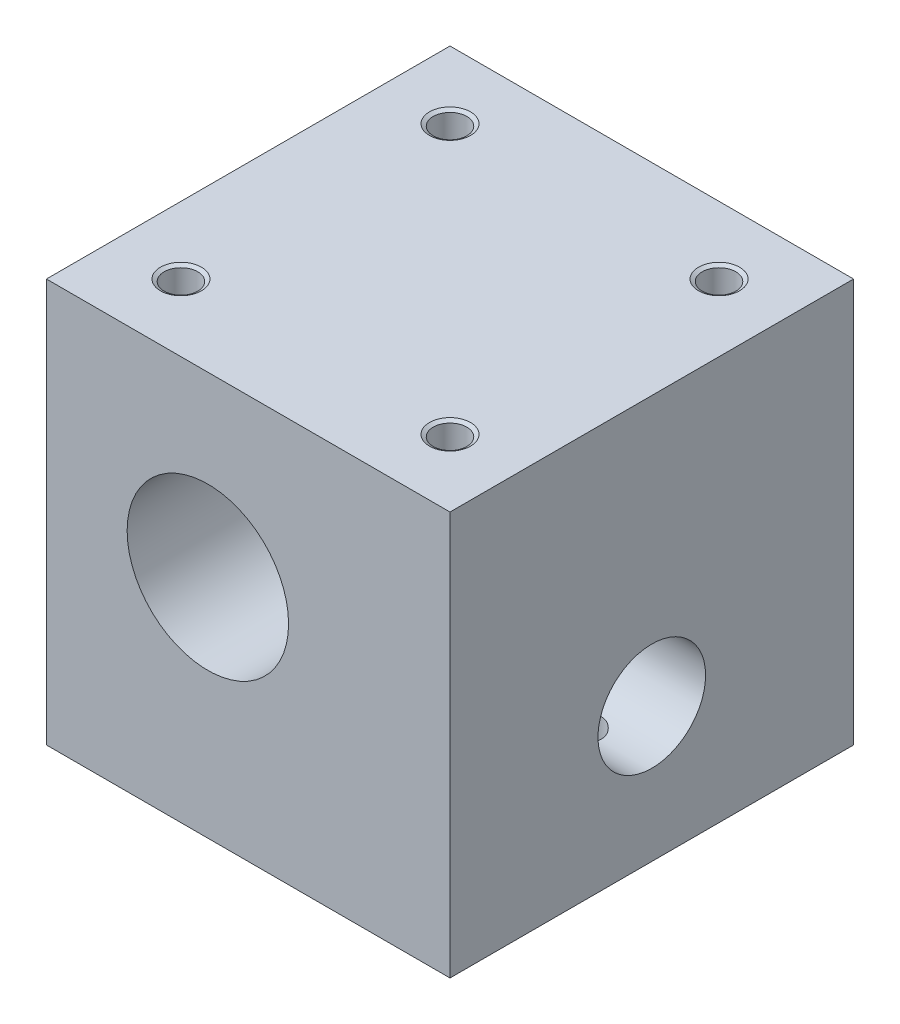
SolidWorks part; units mm, degrees
material "Lega 1060"
ref_plane "Piano frontale" through (0, 0, 0) normal (0, 0, 1) x (1, 0, 0)
ref_plane "Piano superiore" through (0, 0, 0) normal (0, 1, 0) x (1, 0, 0)
ref_plane "Piano destro" through (0, 0, 0) normal (1, 0, 0) x (0, 0, -1)
sketch "Schizzo1" plane through (0, 0, 0) normal (0, 0, 1) x (1, 0, 0)
  line L0 (12, 6.5764) -> (12, 28.444) construction
  line L1 (0, 0) -> (30, 0)
  line L2 (0, 0) -> (0, 30)
  line L3 (0, 30) -> (30, 30)
  line L4 (30, 0) -> (30, 30)
  line L5 (6.315, 16.8) -> (24.6155, 16.8) construction
  circle A0 centre (12, 16.8) radius 6
  dimension "D3" = 12
  dimension "D1" = 30
  dimension "D2" = 30
  dimension "D4" = 12
  dimension "D5" = 13.2
extrude "Estrusione-Estrusione1" add sketch "Schizzo1" along normal blind 30
sketch "Schizzo3" plane through (30, 0, 0) normal (1, 0, 0) x (0, 0, -1)
  line L2 (-15, 10.16) -> (-15, 24.3684) construction
  line L3 (-30, 0) -> (-30, 30) construction
  line L4 (0, 0) -> (0, 30) construction
  line L5 (-30, 0) -> (0, 0) construction
  point P0 (-15, 10)
  dimension "D1" = 10
hole_wizard "Ø8.0 (8) Diameter Hole1" positions "Schizzo5" profile "Schizzo4" hole size "Ø8.0" standard "ISO"
sketch "Schizzo5" plane through (30, 0, 0) normal (1, 0, 0) x (0, 0, -1)
  point P0 (-15, 10)
sketch "Schizzo4" plane through (30, 10, 15) normal (0, 1, 0) x (0, 0, -1)
  line L0 (0, 0) -> (0, 14.4034)
  line L1 (0, 14.4034) -> (4, 12)
  line L2 (4, 12) -> (4, 0)
  line L5 (4, 0) -> (0, 0)
  line L10 (0, 14.4034) -> (-4, 12) construction
  line L11 (0, -6.35) -> (0, 107.95) construction
  dimension "Hole Dia." = 8
  dimension "Hole Depth" = 12
  dimension "Drill Angle" = 118
sketch "Schizzo6" plane through (0, 30, 0) normal (0, 1, 0) x (1, 0, 0)
  line L0 (-7.6843, -25) -> (41.504, -25) construction
  line L1 (0, -30) -> (0, 0) construction
  line L2 (30, -30) -> (0, -30) construction
  point P0 (5, -25)
  point P1 (25, -25)
  dimension "D1" = 20
  dimension "D2" = 5
  dimension "D3" = 5
hole_wizard "Foro filettato M3-1" positions "Schizzo8" profile "Schizzo7" tap size "M3" standard "ISO"
sketch "Schizzo8" plane through (0, 30, 0) normal (0, 1, 0) x (1, 0, 0)
  point P0 (5, -25)
  point P3 (25, -25)
sketch "Schizzo7" plane through (5, 30, 25) normal (1, 0, 0) x (0, 0, 1)
  line L0 (0, 0) -> (0, 9.2511)
  line L1 (0, 9.2511) -> (1.25, 8.5)
  line L2 (1.25, 8.5) -> (1.25, 0.1588)
  line L3 (1.25, 0.1588) -> (1.525, 0)
  line L5 (1.525, 0) -> (0, 0)
  line L6 (-1.25, 0.1588) -> (-1.525, 0) construction
  line L10 (0, 9.2511) -> (-1.25, 8.5) construction
  line L11 (0, -6.35) -> (0, 107.95) construction
  dimension "Tap Drill Dia." = 2.5
  dimension "Tap Drill Depth" = 8.5
  dimension "Near C'Sink Dia." = 3.05
  dimension "Near C'Sink Angle" = 120
  dimension "Drill Angle" = 118
cosmetic thread "Filettatura del foro1"
cosmetic thread "Filettatura del foro2"
ref_plane "Piano1" through (0, 0, 15) normal (0, 0, 1) x (1, 0, 0)
mirror "Specchia1" about plane through (0, 0, 15) normal (0, 0, 1) of "Foro filettato M3-1"
sketch "Sketch1" plane through (0, 0, 0) normal (0, -1, 0) x (1, 0, 0)
  line L0 (30, 15) -> (0, 15) construction
  line L1 (30, 30) -> (30, 0) construction
  line L2 (0, 30) -> (0, 0) construction
  circle A0 centre (25, 15) radius 1.25
  dimension "D1" = 5
  dimension "D2" = 2.5
extrude "Cut-Extrude1" cut sketch "Sketch1" against normal blind 10
